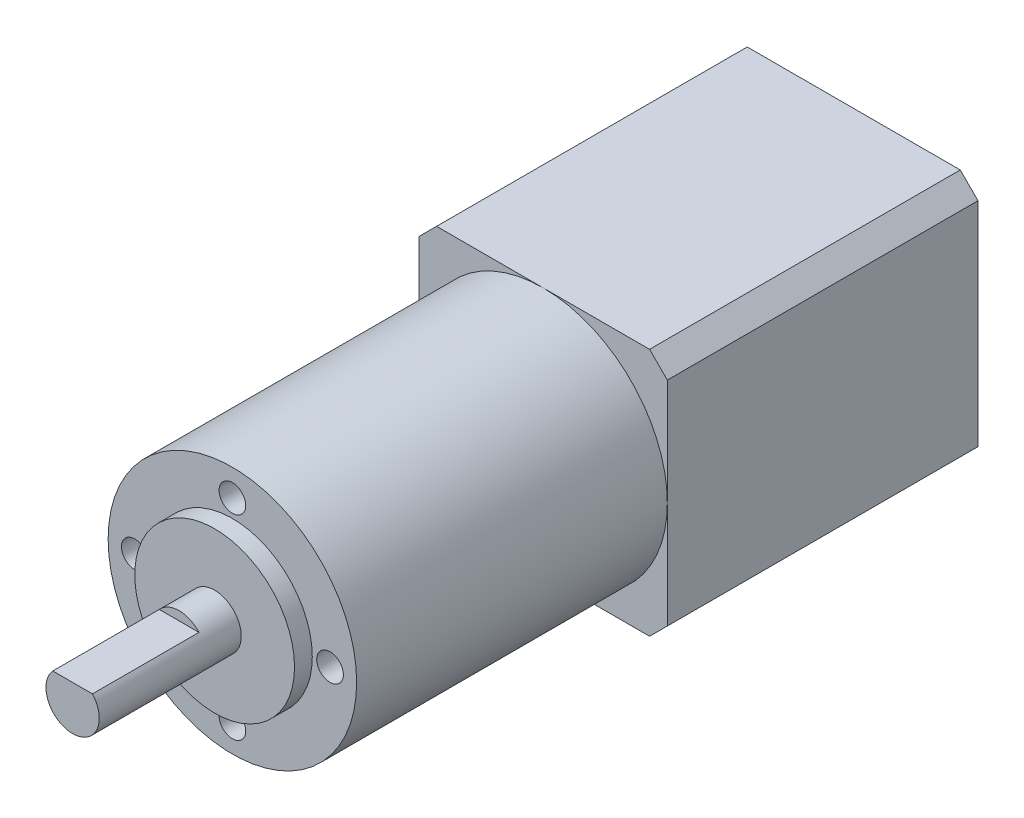
SolidWorks part; units mm, degrees
ref_plane "Front Plane" through (0, 0, 0) normal (0, 0, 1) x (1, 0, 0)
ref_plane "Top Plane" through (0, 0, 0) normal (0, 1, 0) x (1, 0, 0)
ref_plane "Right Plane" through (0, 0, 0) normal (1, 0, 0) x (0, 0, -1)
sketch "Sketch1" plane through (0, 0, 0) normal (0, 0, 1) x (1, 0, 0)
  line L1 (-14, -14) -> (14, -14)
  line L2 (-14, -14) -> (-14, 14)
  line L3 (-14, 14) -> (14, 14)
  line L4 (14, -14) -> (14, 14)
  line L5 (0, 14) -> (0, -14) construction
  line L6 (-14, 0) -> (14, 0) construction
  point P0 (0, 0)
  dimension "D1" = 28
extrude "Boss-Extrude1" add sketch "Sketch1" along normal blind 35
sketch "Sketch2" plane through (0, 0, 35) normal (0, 0, 1) x (1, 0, 0)
  line L0 (14, -14) -> (14, 14) construction
  circle A1 centre (0, 0) radius 14
extrude "Boss-Extrude2" add sketch "Sketch2" along normal blind 35
sketch "Sketch3" plane through (0, 0, 70) normal (0, 0, 1) x (1, 0, 0)
  circle A0 centre (0, 0) radius 9
  dimension "D1" = 18
extrude "Boss-Extrude3" add sketch "Sketch3" along normal blind 2
sketch "Sketch4" plane through (0, 0, 72) normal (0, 0, 1) x (1, 0, 0)
  circle A0 centre (0, 0) radius 3
  dimension "D1" = 6
extrude "Boss-Extrude4" add sketch "Sketch4" along normal blind 16
sketch "Sketch5" plane through (0, 0, 88) normal (0, 0, 1) x (1, 0, 0)
  line L0 (-2.2361, 2) -> (2.2361, 2)
  circle A0 centre (0, 0) radius 3 construction
  arc A1 (-2.2361, 2) -> (2.2361, 2) centre (0, 0) cw
  dimension "D1" = 5
extrude "Cut-Extrude1" cut sketch "Sketch5" against normal blind 12
sketch "Sketch6" plane through (0, 0, 0) normal (0, 0, -1) x (-1, 0, 0)
  line L0 (0, 14) -> (0, -14) construction
  line L1 (-14, 14) -> (14, 14) construction
  line L2 (14, -14) -> (-14, -14) construction
  line L3 (14, 0) -> (-14, 0) construction
  line L4 (14, 14) -> (14, -14) construction
  line L5 (-14, -14) -> (-14, 14) construction
  circle A0 centre (9.5, 0) radius 1.5
  circle A1 centre (-9.5, 0) radius 1.5
  dimension "D1" = 3
  dimension "D2" = 19
extrude "Cut-Extrude2" cut sketch "Sketch6" against normal blind 2
sketch "Sketch7" plane through (0, 0, 0) normal (0, 0, -1) x (-1, 0, 0)
  circle A0 centre (0, 0) radius 2.5
  dimension "D1" = 5
extrude "Boss-Extrude5" add sketch "Sketch7" along normal blind 9.5
chamfer "Chamfer1" distance 2 angle 45 4 edges at (14, -14, 17.5) (14, 14, 17.5) (-14, -14, 17.5) (-14, 14, 17.5)
sketch "Sketch8" plane through (0, 0, 70) normal (0, 0, 1) x (1, 0, 0)
  circle A0 centre (0, 0) radius 11 construction
  circle A1 centre (0, 11) radius 1.5
  circle A2 centre (11, 0) radius 1.5
  circle A3 centre (0, -11) radius 1.5
  circle A4 centre (-11, 0) radius 1.5
  point P14 (0, 0)
  dimension "D1" = 22
  dimension "D2" = 3
  dimension "D3" = 4
extrude "Cut-Extrude3" cut sketch "Sketch8" against normal blind 5
